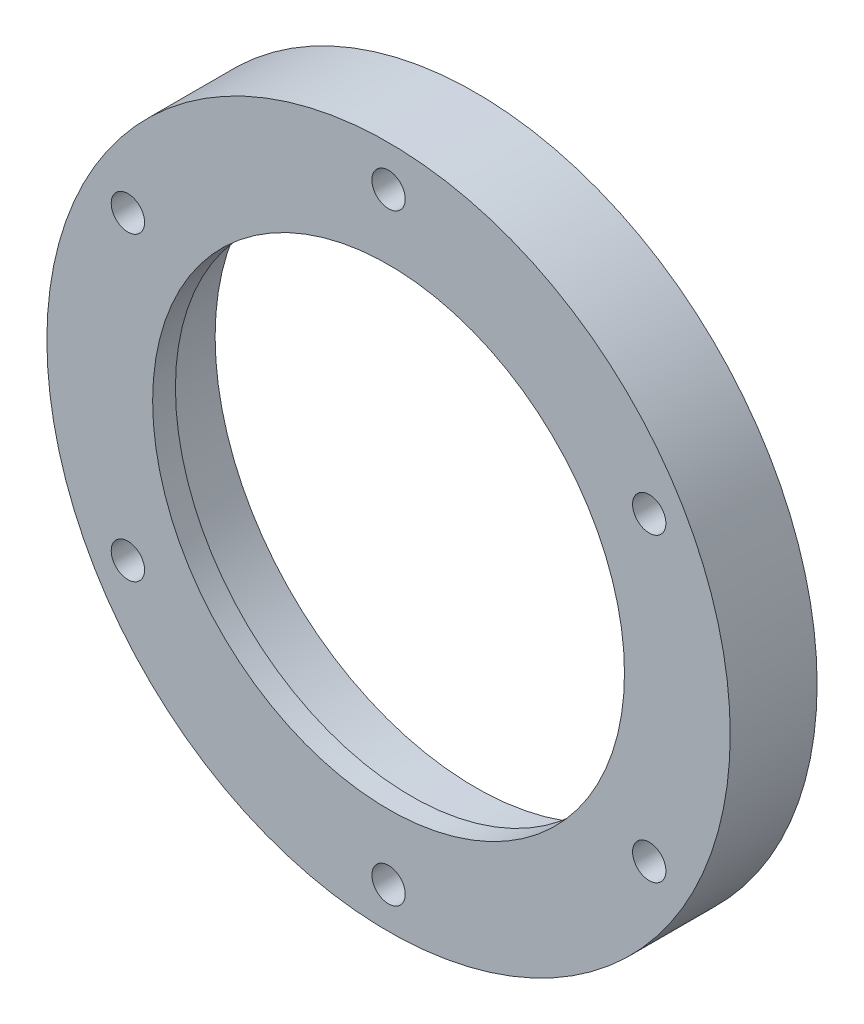
SolidWorks part; units mm, degrees
material "6061 合金"
ref_plane "前视基准面" through (0, 0, 0) normal (0, 0, 1) x (1, 0, 0)
ref_plane "上视基准面" through (0, 0, 0) normal (0, 1, 0) x (1, 0, 0)
ref_plane "右视基准面" through (0, 0, 0) normal (1, 0, 0) x (0, 0, -1)
sketch "草图1" plane through (0, 0, 0) normal (0, 0, 1) x (1, 0, 0)
  circle A0 centre (0, 0) radius 16
  circle A1 centre (0, 0) radius 21
  dimension "D1" = 32
  dimension "D2" = 5
extrude "凸台-拉伸1" add sketch "草图1" along normal mid plane 3.94
sketch "草图2" plane through (0, 0, 1.97) normal (0, 0, 1) x (1, 0, 0)
  circle A0 centre (0, 0) radius 14.5
  circle A1 centre (0, 0) radius 16 construction
  circle A2 centre (0, 0) radius 12.5 construction
  circle A3 centre (0, 0) radius 14 construction
  circle A4 centre (0, 0) radius 21 construction
  circle A5 centre (0, 0) radius 21
  dimension "D1" = 1.5
  dimension "D2" = 25
  dimension "D3" = 1.5
extrude "凸台-拉伸2" add sketch "草图2" along normal blind 1.4
sketch "草图3" plane through (0, 0, 3.37) normal (0, 0, 1) x (1, 0, 0)
  circle A0 centre (0, 0) radius 18.5 construction
  circle A1 centre (0, 0) radius 16 construction
  dimension "D1" = 2.5
hole_wizard "M2.5 螺纹孔1" positions "草图4" profile "草图5" tap size "M2.5" standard "GB" end condition through all
sketch "草图4" plane through (0, 0, -1.97) normal (0, 0, -1) x (-1, 0, 0)
  line L0 (0, 18.5) -> (0, 0) construction
  circle A0 centre (0, 0) radius 18.5 construction
  point P0 (0, 18.5)
sketch "草图5" plane through (0, 18.5, -1.97) normal (1, 0, 0) x (0, 1, 0)
  line L0 (0, 0) -> (0, 5.34)
  line L1 (0, 5.34) -> (1.025, 5.34)
  line L2 (1.025, 5.34) -> (1.025, 0)
  line L5 (1.025, 0) -> (0, 0)
  line L11 (0, -6.35) -> (0, 107.95) construction
  dimension "通孔螺纹孔钻头直径" = 2.05
  dimension "通孔螺纹孔钻头深度" = 5.34
cosmetic thread "孔螺蚊线1" parameters "D2"=2.5
pattern_circular "阵列(圆周)1" count 6 over 360 about axis through (0, 0, 0) along (0, 0, 1) of "M2.5 螺纹孔1"
cosmetic thread "孔螺蚊线2" parameters "D2"=2.5
cosmetic thread "孔螺蚊线3" parameters "D2"=2.5
cosmetic thread "孔螺蚊线4" parameters "D2"=2.5
cosmetic thread "孔螺蚊线5" parameters "D2"=2.5
cosmetic thread "孔螺蚊线6" parameters "D2"=2.5
